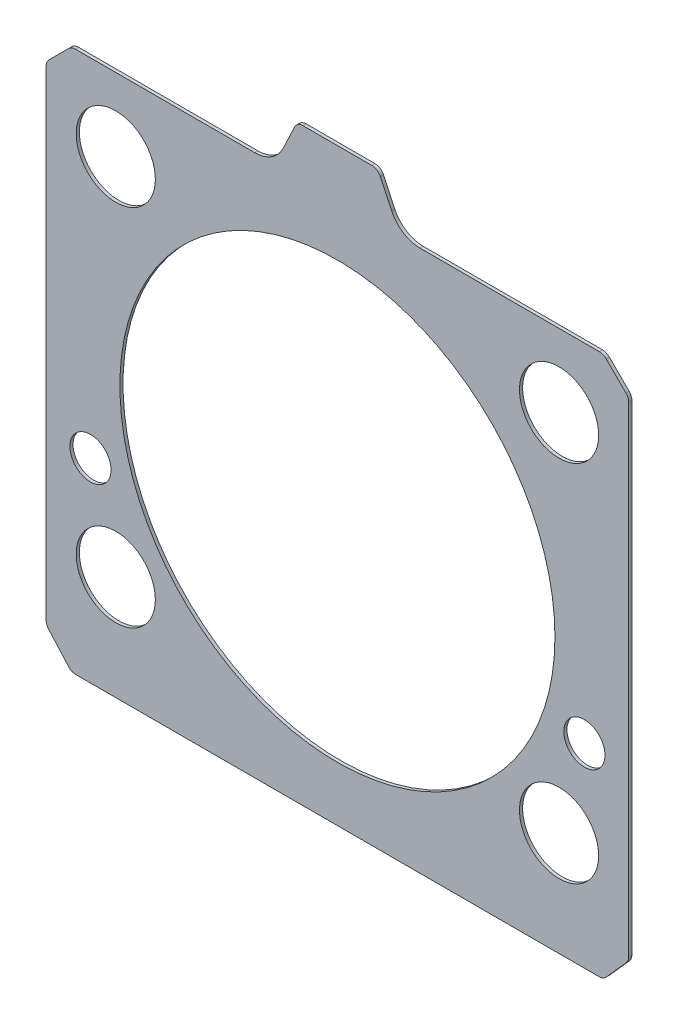
SolidWorks part; units mm, degrees
material "TESNIT BA-R"
ref_plane "Front Plane" through (0, 0, 0) normal (0, 0, 1) x (1, 0, 0)
ref_plane "Top Plane" through (0, 0, 0) normal (0, 1, 0) x (1, 0, 0)
ref_plane "Right Plane" through (0, 0, 0) normal (1, 0, 0) x (0, 0, -1)
sketch "Sketch1" plane through (0, 0, 0) normal (0, 0, 1) x (1, 0, 0)
  line L0 (0, 0) -> (0, 130.6784) construction
  line L1 (84, 85) -> (92, 77)
  line L2 (-92, -77) -> (-84, -86)
  line L3 (92, -77) -> (84, -86)
  line L25 (-84, -86) -> (84, -86)
  line L27 (92, -77) -> (92, 77)
  line L29 (84, 85) -> (19.8, 85)
  line L30 (19.8, 85) -> (12.75, 100)
  line L31 (12.75, 100) -> (-12.75, 100)
  line L32 (-12.75, 100) -> (-19.8, 85)
  line L33 (-19.8, 85) -> (-84, 85)
  line L34 (-84, 85) -> (-92, 77)
  line L35 (-92, 77) -> (-92, -77)
  circle A0 centre (-78, -24.5) radius 6.5
  circle A1 centre (0, 0) radius 68.7
  circle A6 centre (-70, 62) radius 12.5
  circle A7 centre (70, 62) radius 12.5
  circle A8 centre (-70, -53) radius 12.5
  circle A9 centre (70, -53) radius 12.5
  circle A10 centre (78, -24.5) radius 6.5
  dimension "D2" = 13
  dimension "D3" = 78
  dimension "D4" = 24.5
  dimension "D6" = 137.4
  dimension "D7" = 86
  dimension "D13" = 140
  dimension "D14" = 25
  dimension "D15" = 62
  dimension "D16" = 53
  dimension "D17" = 39.6
  dimension "D19" = 25.5
  dimension "D5" = 184
  dimension "D8" = 85
  dimension "D9" = 8
  dimension "D10" = 8
  dimension "D11" = 9
  dimension "D12" = 8
  dimension "D18" = 100
extrude "Extrude1" add sketch "Sketch1" along normal blind 1
fillet "Fillet1" radius 10 2 edges at (19.8, 85, 0.5) (-19.8, 85, 0.5)
fillet "Fillet2" radius 3 10 edges at (-84, -86, 0.5) (-92, -77, 0.5) (84, -86, 0.5) (92, -77, 0.5) (92, 77, 0.5) (84, 85, 0.5) (-84, 85, 0.5) (-92, 77, 0.5) (12.75, 100, 0.5) (-12.75, 100, 0.5)
